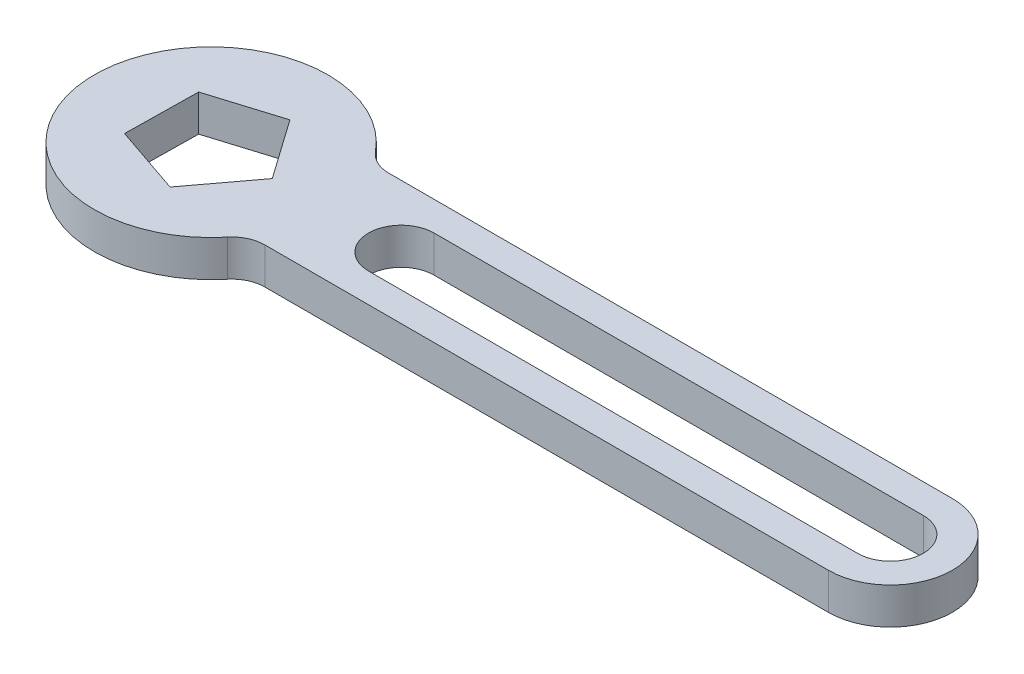
SolidWorks part; units mm, degrees
ref_plane "Front Plane" through (0, 0, 0) normal (0, 0, 1) x (1, 0, 0)
ref_plane "Top Plane" through (0, 0, 0) normal (0, 1, 0) x (1, 0, 0)
ref_plane "Right Plane" through (0, 0, 0) normal (1, 0, 0) x (0, 0, -1)
sketch "Sketch1" plane through (0, 0, 0) normal (0, 1, 0) x (1, 0, 0)
  line L4 (-134, 17) -> (0, 17)
  line L6 (-134, 17) -> (-154.4025, 17)
  line L7 (-180.6084, 16.1009) -> (-199.7188, 10.2023)
  line L8 (-199.7188, 10.2023) -> (-200.0144, -9.7955)
  line L9 (-200.0144, -9.7955) -> (-181.0867, -16.2563)
  line L10 (-181.0867, -16.2563) -> (-169.0931, -0.2514)
  line L11 (-169.0931, -0.2514) -> (-180.6084, 16.1009)
  line L12 (-134, -17) -> (0, -17)
  line L13 (-134, -17) -> (-154.4025, -17)
  line L14 (-134, 9) -> (0, 9)
  line L15 (0, -9) -> (-134, -9)
  arc A0 (0, -9) -> (0, 9) centre (0, 0) ccw
  arc A1 (0, -17) -> (0, 17) centre (0, 0) ccw
  arc A3 (-134, 9) -> (-134, -9) centre (-134, 0) ccw
  circle A4 centre (-186.1043, 0) radius 32
  circle A5 centre (-186.1043, 0) radius 13.7638 construction
  arc A8 (-161.3615, 20.2927) -> (-154.4025, 17) centre (-154.4025, 26) ccw
  arc A9 (-161.3615, -20.2927) -> (-154.4025, -17) centre (-154.4025, -26) cw
  dimension "D1" = 18
  dimension "D2" = 34
  dimension "D5" = 64
  dimension "D3" = 134
extrude "Boss-Extrude1" add sketch "Sketch1" along normal blind 10 contours A4 L11 L10 L9 L8 L7 | A4 A9 L13 L12 A1 L4 L6 A8 A3 L14 A0 L15
